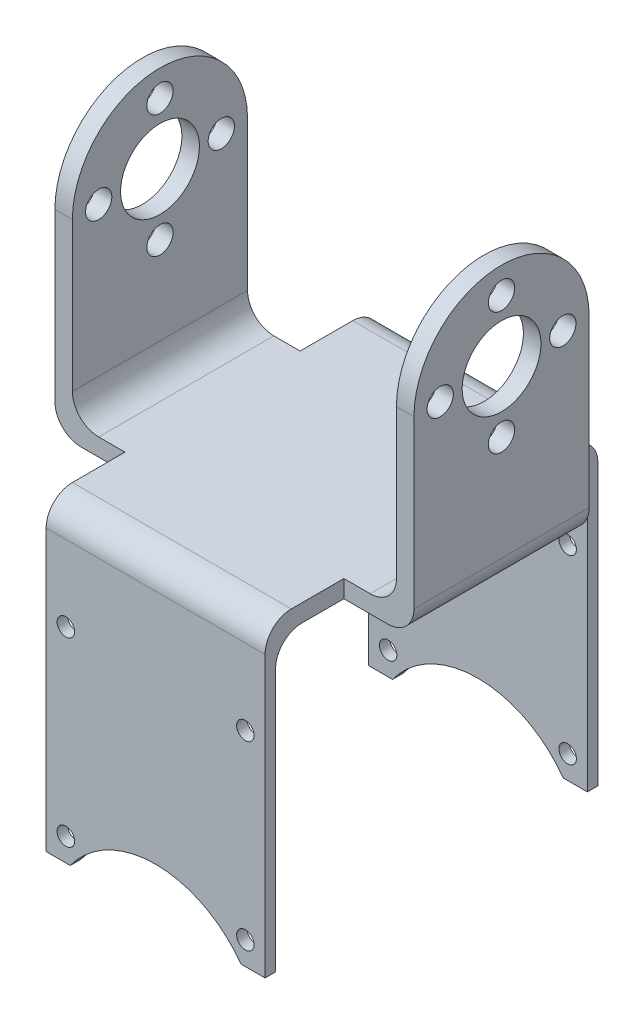
SolidWorks part; units mm, degrees
ref_plane "前视基准面" through (0, 0, 0) normal (0, 0, 1) x (1, 0, 0)
ref_plane "上视基准面" through (0, 0, 0) normal (0, 1, 0) x (1, 0, 0)
ref_plane "右视基准面" through (0, 0, 0) normal (1, 0, 0) x (0, 0, -1)
sketch "草图1" plane through (0, 0, 0) normal (0, 1, 0) x (1, 0, 0)
  line L0 (12.5, -10) -> (12.5, -19)
  line L1 (-20.5, 10) -> (-12.5, 10)
  line L2 (-20.5, 10) -> (-20.5, -10)
  line L3 (-20.5, -10) -> (-12.5, -10)
  line L4 (20.5, 10) -> (20.5, -10)
  line L5 (-20.5, 10) -> (20.5, -10) construction
  line L6 (-20.5, -10) -> (20.5, 10) construction
  line L7 (-12.5, 19) -> (12.5, 19)
  line L8 (-12.5, 19) -> (-12.5, 10)
  line L9 (-12.5, -19) -> (12.5, -19)
  line L10 (12.5, 19) -> (12.5, 10)
  line L11 (-12.5, 19) -> (12.5, -19) construction
  line L12 (-12.5, -19) -> (12.5, 19) construction
  line L13 (12.5, -10) -> (20.5, -10)
  line L14 (-12.5, -10) -> (-12.5, -19)
  line L15 (12.5, 10) -> (20.5, 10)
  point P0 (0, 0)
  point P6 (0, 0)
  dimension "D1" = 41
  dimension "D2" = 20
  dimension "D3" = 25
  dimension "D4" = 38
extrude "凸台-拉伸1" add sketch "草图1" along normal blind 2
sketch "草图2" plane through (0, 2, 0) normal (0, 1, 0) x (1, 0, 0)
  line L0 (-20.5, -10) -> (-12.5, -10) construction
  line L1 (-20.5, 10) -> (-18.5, 10)
  line L2 (-20.5, 10) -> (-20.5, -10)
  line L3 (-20.5, -10) -> (-18.5, -10)
  line L4 (-18.5, 10) -> (-18.5, -10)
  line L5 (12.5, -10) -> (20.5, -10) construction
  line L6 (20.5, 10) -> (18.5, 10)
  line L7 (20.5, 10) -> (20.5, -10)
  line L8 (20.5, -10) -> (18.5, -10)
  line L9 (18.5, 10) -> (18.5, -10)
  dimension "D1" = 2
  dimension "D2" = 2
extrude "凸台-拉伸2" add sketch "草图2" along normal blind 40
fillet "圆角1" radius 3 4 edges at (-20.5, 0, 0) (-18.5, 2, 0) (18.5, 2, 0) (20.5, 0, 0)
sketch "草图4" plane through (0, 0, 0) normal (0, -1, 0) x (1, 0, 0)
  line L0 (12.5, 19) -> (12.5, 10) construction
  line L1 (-12.5, 19) -> (12.5, 19)
  line L2 (-12.5, 19) -> (-12.5, 17.8)
  line L3 (-12.5, 17.8) -> (12.5, 17.8)
  line L4 (12.5, 19) -> (12.5, 17.8)
  line L5 (-12.5, -19) -> (-12.5, -10) construction
  line L6 (12.5, -19) -> (-12.5, -19)
  line L7 (12.5, -19) -> (12.5, -17.8)
  line L8 (12.5, -17.8) -> (-12.5, -17.8)
  line L9 (-12.5, -19) -> (-12.5, -17.8)
  dimension "D1" = 1.2
  dimension "D2" = 1.2
extrude "凸台-拉伸3" add sketch "草图4" along normal blind 40
fillet "圆角2" radius 3 4 edges at (0, 0, -17.8) (0, 2, -19) (0, 2, 19) (0, 0, 17.8)
sketch "草图5" plane through (0, 0, -19) normal (0, 0, -1) x (-1, 0, 0)
  line L0 (0, -46.7705) -> (0, 23.5536) construction
  line L1 (-25.8926, 0) -> (22.9009, 0) construction
  line L2 (12.5, -1) -> (12.5, -40) construction
  line L3 (-12.5, -1) -> (-12.5, -40) construction
  line L4 (-12.5, -20) -> (-12.5, -40)
  line L5 (-12.5, -40) -> (12.5, -40)
  line L6 (12.5, -40) -> (12.5, -20)
  arc A0 (12.5, -20) -> (-12.5, -20) centre (0, -20) cw
  circle A1 centre (0, -20) radius 4.5
  circle A2 centre (0, -20) radius 7 construction
  circle A3 centre (0, -13) radius 1.5
  circle A4 centre (7, -20) radius 1.5
  circle A5 centre (0, -27) radius 1.5
  circle A6 centre (-7, -20) radius 1.5
  point P29 (0, -20)
  dimension "D2" = 9
  dimension "D3" = 14
  dimension "D4" = 3
  dimension "D1" = 20
  dimension "D5" = 4
extrude "切除-拉伸1" [suppressed] cut sketch "草图5" against normal through all
sketch "草图6" plane through (-20.5, 0, 0) normal (-1, 0, 0) x (0, 0, 1)
  line L0 (0, 47.2402) -> (0, -12.4121) construction
  line L1 (26.009, 2) -> (-24.6618, 2) construction
  line L2 (-10, 42) -> (-10, 3) construction
  line L3 (10, 42) -> (10, 3) construction
  line L4 (-10, 22) -> (-10, 42)
  line L5 (-10, 42) -> (10, 42)
  line L6 (10, 42) -> (10, 22)
  arc A0 (-10, 22) -> (10, 22) centre (0, 22) cw
  circle A1 centre (0, 22) radius 4.5
  circle A2 centre (0, 22) radius 7 construction
  circle A3 centre (0, 15) radius 1.5
  circle A4 centre (-7, 22) radius 1.5
  circle A5 centre (0, 29) radius 1.5
  circle A6 centre (7, 22) radius 1.5
  point P29 (0, 22)
  dimension "D2" = 9
  dimension "D4" = 14
  dimension "D5" = 3
  dimension "D1" = 2
  dimension "D3" = 20
  dimension "D6" = 4
extrude "切除-拉伸2" cut sketch "草图6" against normal through all
sketch "草图7" plane through (0, 0, 19) normal (0, 0, 1) x (1, 0, 0)
  line L0 (0, -46.3202) -> (0, 14.2704) construction
  line L1 (-25.5668, 0) -> (26.1896, 0) construction
  line L2 (-12.5, -33) -> (-9.7468, -33)
  line L3 (-10.25, -30.35) -> (10.25, -30.35) construction
  line L4 (-10.25, -30.35) -> (-10.25, -9.65) construction
  line L5 (-10.25, -9.65) -> (10.25, -9.65) construction
  line L6 (10.25, -30.35) -> (10.25, -9.65) construction
  line L7 (-10.25, -30.35) -> (10.25, -9.65) construction
  line L8 (-10.25, -9.65) -> (10.25, -30.35) construction
  line L9 (-12.5, -1) -> (-12.5, -40) construction
  line L10 (12.5, -1) -> (12.5, -40) construction
  line L11 (12.5, -33) -> (12.5, -40)
  line L12 (12.5, -40) -> (-12.5, -40)
  line L13 (-12.5, -40) -> (-12.5, -33)
  line L14 (9.7468, -33) -> (12.5, -33)
  circle A0 centre (-10.25, -30.35) radius 1
  circle A1 centre (-10.25, -9.65) radius 1
  circle A2 centre (10.25, -9.65) radius 1
  circle A3 centre (10.25, -30.35) radius 1
  arc A4 (-9.7468, -33) -> (9.7468, -33) centre (0, -40) cw
  point P5 (0, -20)
  dimension "D4" = 2
  dimension "D5" = 2
  dimension "D6" = 2
  dimension "D7" = 2
  dimension "D10" = 12
  dimension "D1" = 20.5
  dimension "D2" = 20.7
  dimension "D3" = 20
  dimension "D8" = 33
  dimension "D9" = 40
extrude "切除-拉伸3" cut sketch "草图7" against normal through all
